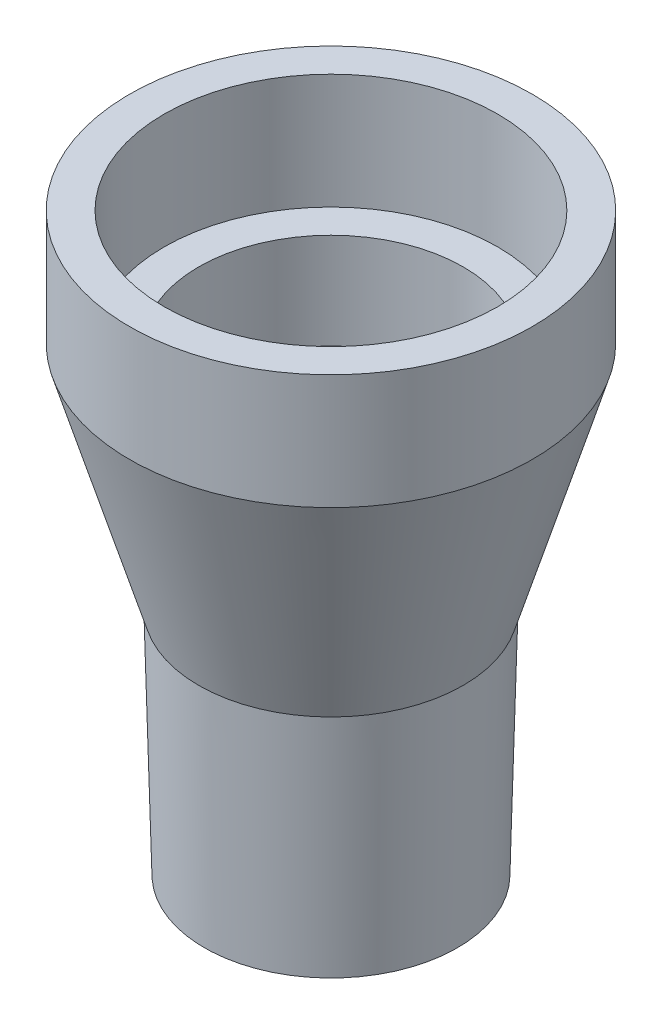
SolidWorks part; units mm, degrees
ref_plane "Front Plane" through (0, 0, 0) normal (0, 0, 1) x (1, 0, 0)
ref_plane "Top Plane" through (0, 0, 0) normal (0, 1, 0) x (1, 0, 0)
ref_plane "Right Plane" through (0, 0, 0) normal (1, 0, 0) x (0, 0, -1)
sketch "Sketch1" plane through (0, 0, 0) normal (0, 0, 1) x (1, 0, 0)
  line L0 (0, 0) -> (0, 57.5749) construction
  line L1 (14.5, 40) -> (14.5, 50)
  line L2 (14.5, 50) -> (17.5, 50)
  line L3 (17.5, 50) -> (17.5, 40)
  line L4 (17.5, 40) -> (11.5, 20)
  line L5 (11.5, 20) -> (11, 0)
  line L6 (11, 0) -> (8, 0)
  line L7 (14.5, 40) -> (11.5, 40)
  line L8 (8, 20) -> (8, 0)
  line L10 (11.5, 40) -> (11.5, 31.6667)
  line L11 (11.5, 31.6667) -> (8, 20)
  line L12 (11.5, 20) -> (8, 20) construction
  dimension "D1" = 3
  dimension "D2" = 3
  dimension "D3" = 20
  dimension "D4" = 10
  dimension "D5" = 29
  dimension "D6" = 20
  dimension "D7" = 23
  dimension "D8" = 22
  dimension "D9" = 3
revolve "Revolve1" add sketch "Sketch1" angle 360 about L0
